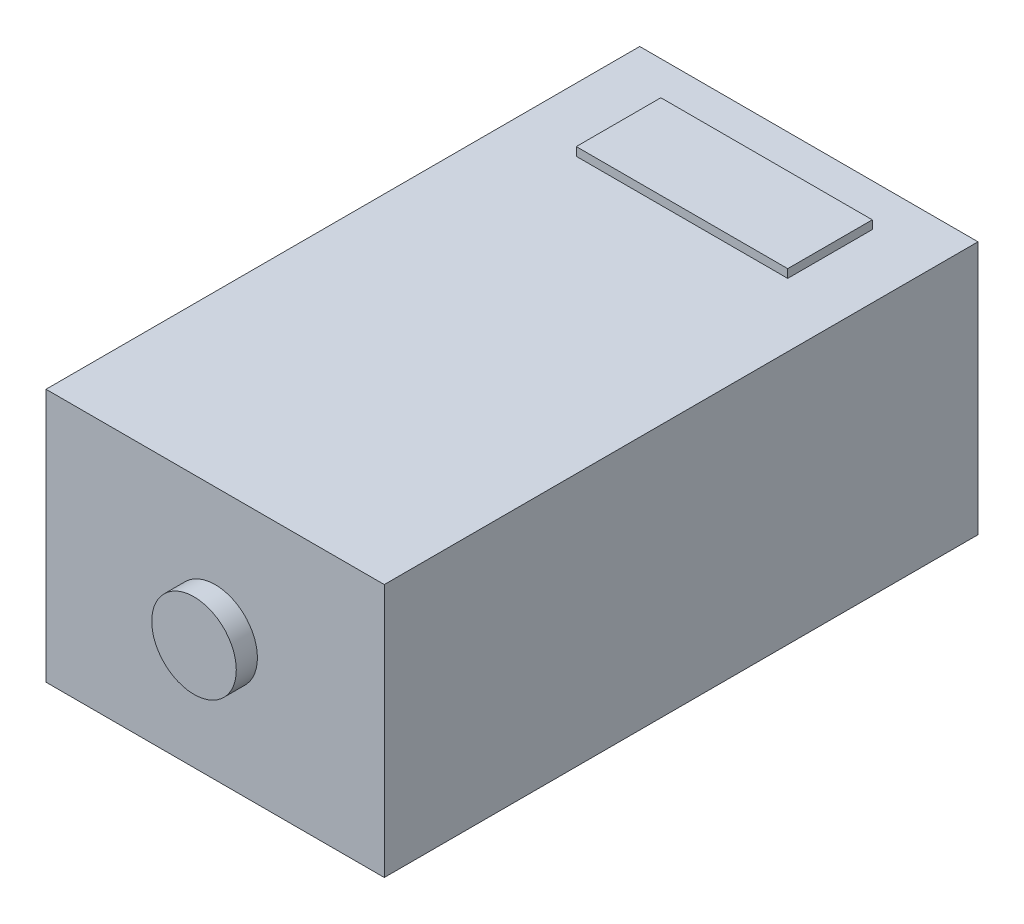
SolidWorks part; units mm, degrees
ref_plane "Спереди" through (0, 0, 0) normal (0, 0, 1) x (1, 0, 0)
ref_plane "Сверху" through (0, 0, 0) normal (0, 1, 0) x (1, 0, 0)
ref_plane "Справа" through (0, 0, 0) normal (1, 0, 0) x (0, 0, -1)
sketch "Эскиз1" plane through (0, 0, 0) normal (0, 0, 1) x (1, 0, 0)
  line L1 (0, 0) -> (400, 0)
  line L2 (0, 0) -> (0, 300)
  line L3 (0, 300) -> (400, 300)
  line L4 (400, 0) -> (400, 300)
  dimension "D1" = 300
  dimension "D2" = 400
extrude "Бобышка-Вытянуть1" add sketch "Эскиз1" along normal blind 702
sketch "Эскиз2" plane through (0, 0, 0) normal (0, 0, -1) x (-1, 0, 0)
  line L0 (-332, 60) -> (-400, 60) construction
  line L1 (-400, 0) -> (-400, 300) construction
  line L2 (-68, 60) -> (0, 60) construction
  line L5 (0, 0) -> (-400, 0) construction
  circle A0 centre (-332, 60) radius 13.4
  circle A1 centre (-267, 30) radius 10.65
  circle A2 centre (-165, 200) radius 13.4
  circle A3 centre (-133, 30) radius 10.65
  circle A4 centre (-68, 60) radius 13.4
  point P10 (0, 0)
  point P15 (0, 0)
  point P19 (0, 0)
  dimension "D5" = 30
  dimension "D8" = 21.3
  dimension "D9" = 26.8
  dimension "D1" = 102
  dimension "D2" = 65
  dimension "D3" = 32
  dimension "D4" = 65
  dimension "D6" = 200
  dimension "D7" = 60
extrude "Бобышка-Вытянуть2" add sketch "Эскиз2" along normal blind 25
sketch "Эскиз3" plane through (0, 0, 702) normal (0, 0, 1) x (1, 0, 0)
  line L0 (0, 0) -> (400, 0) construction
  line L1 (400, 150) -> (0, 150) construction
  line L2 (400, 0) -> (400, 300) construction
  line L3 (0, 300) -> (0, 0) construction
  circle A0 centre (200, 150) radius 50
  dimension "D1" = 100
  dimension "D2" = 150
extrude "Бобышка-Вытянуть3" add sketch "Эскиз3" along normal blind 25
sketch "Эскиз4" plane through (0, 300, 0) normal (0, 1, 0) x (1, 0, 0)
  line L0 (400, 0) -> (0, 0) construction
  line L5 (75, -50) -> (325, -50)
  line L6 (75, -50) -> (75, -150)
  line L7 (75, -150) -> (325, -150)
  line L8 (325, -50) -> (325, -150)
  line L9 (75, -50) -> (325, -150) construction
  line L10 (75, -150) -> (325, -50) construction
  line L11 (400, -100) -> (0, -100) construction
  line L12 (400, -702) -> (400, 0) construction
  line L13 (0, -702) -> (0, 0) construction
  point P0 (200, -100)
  dimension "D1" = 250
  dimension "D2" = 100
  dimension "D3" = 100
extrude "Бобышка-Вытянуть4" add sketch "Эскиз4" along normal blind 10
